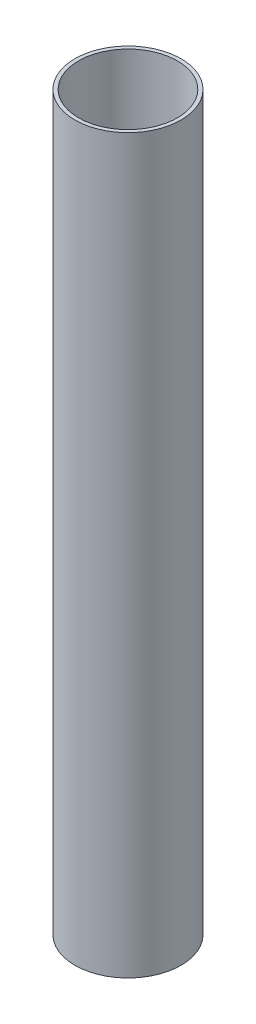
SolidWorks part; units mm, degrees
ref_plane "Front Plane" through (0, 0, 0) normal (0, 0, 1) x (1, 0, 0)
ref_plane "Top Plane" through (0, 0, 0) normal (0, 1, 0) x (1, 0, 0)
ref_plane "Right Plane" through (0, 0, 0) normal (1, 0, 0) x (0, 0, -1)
sketch "Sketch1" plane through (0, 0, 0) normal (0, 1, 0) x (1, 0, 0)
  circle A0 centre (0, 0) radius 27
  circle A1 centre (0, 0) radius 29
  dimension "D1" = 58
  dimension "D2" = 2
extrude "Boss-Extrude1" add sketch "Sketch1" along normal blind 400
